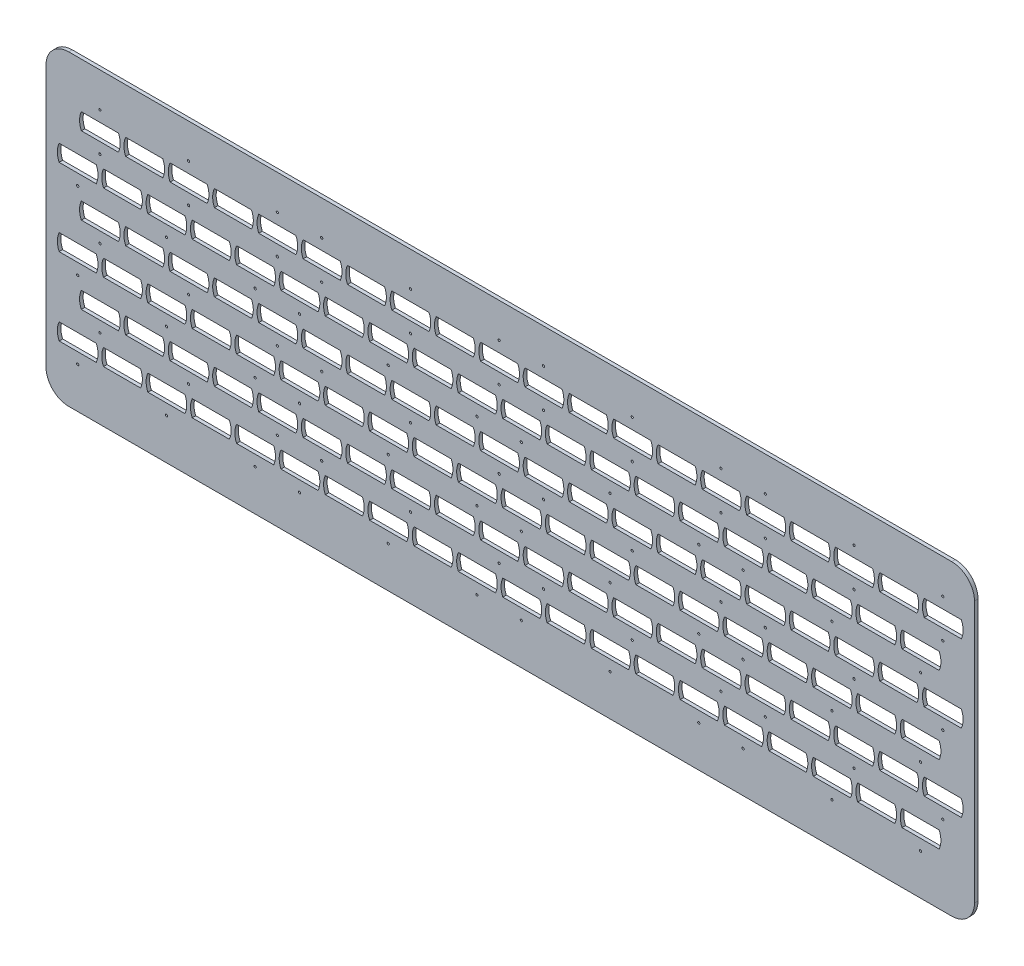
SolidWorks part; units mm, degrees
material "Custom Plastic"
ref_plane "X-Y Datum" through (0, 0, 0) normal (0, 0, 1) x (1, 0, 0)
ref_plane "X-Z Datum" through (0, 0, 0) normal (0, 1, 0) x (1, 0, 0)
ref_plane "Y-Z Datum" through (0, 0, 0) normal (1, 0, 0) x (0, 0, -1)
sketch "Sketch1" plane through (0, 0, 0) normal (0, 0, 1) x (1, 0, 0)
  line L0 (0, 0) -> (0, 17.78) construction
  line L1 (0, 0) -> (414.644, 0)
  line L2 (0, 0) -> (0, 137.1309)
  line L3 (0, 137.1309) -> (414.644, 137.1309)
  line L4 (414.644, 0) -> (414.644, 137.1309)
  line L5 (400.489, 122.1757) -> (400.489, 137.1309) construction
  line L6 (409.564, 113.1007) -> (414.644, 113.1007) construction
  line L7 (14.155, 17.78) -> (14.155, 0) construction
  line L8 (5.08, 26.855) -> (0, 26.855) construction
  circle A0 centre (14.155, 26.855) radius 9.075
  circle A1 centre (33.967, 26.855) radius 9.075
  circle A2 centre (53.779, 26.855) radius 9.075
  circle A3 centre (73.591, 26.855) radius 9.075
  circle A4 centre (93.403, 26.855) radius 9.075
  circle A5 centre (113.215, 26.855) radius 9.075
  circle A6 centre (133.027, 26.855) radius 9.075
  circle A7 centre (152.839, 26.855) radius 9.075
  circle A8 centre (172.651, 26.855) radius 9.075
  circle A9 centre (192.463, 26.855) radius 9.075
  circle A10 centre (212.275, 26.855) radius 9.075
  circle A11 centre (232.087, 26.855) radius 9.075
  circle A12 centre (251.899, 26.855) radius 9.075
  circle A13 centre (271.711, 26.855) radius 9.075
  circle A14 centre (291.523, 26.855) radius 9.075
  circle A15 centre (311.335, 26.855) radius 9.075
  circle A16 centre (331.147, 26.855) radius 9.075
  circle A17 centre (350.959, 26.855) radius 9.075
  circle A18 centre (370.771, 26.855) radius 9.075
  circle A19 centre (390.583, 26.855) radius 9.075
  circle A20 centre (43.873, 44.0127) radius 9.075
  circle A21 centre (63.685, 44.0127) radius 9.075
  circle A22 centre (83.497, 44.0127) radius 9.075
  circle A23 centre (103.309, 44.0127) radius 9.075
  circle A24 centre (123.121, 44.0127) radius 9.075
  circle A25 centre (142.933, 44.0127) radius 9.075
  circle A26 centre (162.745, 44.0127) radius 9.075
  circle A27 centre (182.557, 44.0127) radius 9.075
  circle A28 centre (202.369, 44.0127) radius 9.075
  circle A29 centre (222.181, 44.0127) radius 9.075
  circle A30 centre (241.993, 44.0127) radius 9.075
  circle A31 centre (261.805, 44.0127) radius 9.075
  circle A32 centre (281.617, 44.0127) radius 9.075
  circle A33 centre (301.429, 44.0127) radius 9.075
  circle A34 centre (321.241, 44.0127) radius 9.075
  circle A35 centre (341.053, 44.0127) radius 9.075
  circle A36 centre (360.865, 44.0127) radius 9.075
  circle A37 centre (380.677, 44.0127) radius 9.075
  circle A38 centre (400.489, 44.0127) radius 9.075
  circle A39 centre (24.061, 44.0127) radius 9.075
  circle A40 centre (14.155, 61.399) radius 9.075
  circle A41 centre (33.967, 61.399) radius 9.075
  circle A42 centre (53.779, 61.399) radius 9.075
  circle A43 centre (73.591, 61.399) radius 9.075
  circle A44 centre (93.403, 61.399) radius 9.075
  circle A45 centre (113.215, 61.399) radius 9.075
  circle A46 centre (133.027, 61.399) radius 9.075
  circle A47 centre (152.839, 61.399) radius 9.075
  circle A48 centre (172.651, 61.399) radius 9.075
  circle A49 centre (192.463, 61.399) radius 9.075
  circle A50 centre (212.275, 61.399) radius 9.075
  circle A51 centre (232.087, 61.399) radius 9.075
  circle A52 centre (251.899, 61.399) radius 9.075
  circle A53 centre (271.711, 61.399) radius 9.075
  circle A54 centre (291.523, 61.399) radius 9.075
  circle A55 centre (311.335, 61.399) radius 9.075
  circle A56 centre (331.147, 61.399) radius 9.075
  circle A57 centre (350.959, 61.399) radius 9.075
  circle A58 centre (370.771, 61.399) radius 9.075
  circle A59 centre (390.583, 61.399) radius 9.075
  circle A60 centre (43.873, 78.5567) radius 9.075
  circle A61 centre (63.685, 78.5567) radius 9.075
  circle A62 centre (83.497, 78.5567) radius 9.075
  circle A63 centre (103.309, 78.5567) radius 9.075
  circle A64 centre (123.121, 78.5567) radius 9.075
  circle A65 centre (142.933, 78.5567) radius 9.075
  circle A66 centre (162.745, 78.5567) radius 9.075
  circle A67 centre (182.557, 78.5567) radius 9.075
  circle A68 centre (202.369, 78.5567) radius 9.075
  circle A69 centre (222.181, 78.5567) radius 9.075
  circle A70 centre (241.993, 78.5567) radius 9.075
  circle A71 centre (261.805, 78.5567) radius 9.075
  circle A72 centre (281.617, 78.5567) radius 9.075
  circle A73 centre (301.429, 78.5567) radius 9.075
  circle A74 centre (321.241, 78.5567) radius 9.075
  circle A75 centre (341.053, 78.5567) radius 9.075
  circle A76 centre (360.865, 78.5567) radius 9.075
  circle A77 centre (380.677, 78.5567) radius 9.075
  circle A78 centre (400.489, 78.5567) radius 9.075
  circle A79 centre (24.061, 78.5567) radius 9.075
  circle A80 centre (14.155, 95.943) radius 9.075
  circle A81 centre (33.967, 95.943) radius 9.075
  circle A82 centre (53.779, 95.943) radius 9.075
  circle A83 centre (73.591, 95.943) radius 9.075
  circle A84 centre (93.403, 95.943) radius 9.075
  circle A85 centre (113.215, 95.943) radius 9.075
  circle A86 centre (133.027, 95.943) radius 9.075
  circle A87 centre (152.839, 95.943) radius 9.075
  circle A88 centre (172.651, 95.943) radius 9.075
  circle A89 centre (192.463, 95.943) radius 9.075
  circle A90 centre (212.275, 95.943) radius 9.075
  circle A91 centre (232.087, 95.943) radius 9.075
  circle A92 centre (251.899, 95.943) radius 9.075
  circle A93 centre (271.711, 95.943) radius 9.075
  circle A94 centre (291.523, 95.943) radius 9.075
  circle A95 centre (311.335, 95.943) radius 9.075
  circle A96 centre (331.147, 95.943) radius 9.075
  circle A97 centre (350.959, 95.943) radius 9.075
  circle A98 centre (370.771, 95.943) radius 9.075
  circle A99 centre (390.583, 95.943) radius 9.075
  circle A100 centre (43.873, 113.1007) radius 9.075
  circle A101 centre (63.685, 113.1007) radius 9.075
  circle A102 centre (83.497, 113.1007) radius 9.075
  circle A103 centre (103.309, 113.1007) radius 9.075
  circle A104 centre (123.121, 113.1007) radius 9.075
  circle A105 centre (142.933, 113.1007) radius 9.075
  circle A106 centre (162.745, 113.1007) radius 9.075
  circle A107 centre (182.557, 113.1007) radius 9.075
  circle A108 centre (202.369, 113.1007) radius 9.075
  circle A109 centre (222.181, 113.1007) radius 9.075
  circle A110 centre (241.993, 113.1007) radius 9.075
  circle A111 centre (261.805, 113.1007) radius 9.075
  circle A112 centre (281.617, 113.1007) radius 9.075
  circle A113 centre (301.429, 113.1007) radius 9.075
  circle A114 centre (321.241, 113.1007) radius 9.075
  circle A115 centre (341.053, 113.1007) radius 9.075
  circle A116 centre (360.865, 113.1007) radius 9.075
  circle A117 centre (380.677, 113.1007) radius 9.075
  circle A118 centre (400.489, 113.1007) radius 9.075
  circle A119 centre (24.061, 113.1007) radius 9.075
  dimension "D1" = 20
  dimension "D2" = 2
  dimension "D3" = 3
extrude "Plate thickness" add sketch "Sketch1" along normal blind 1.5748
sketch "Sketch2" plane through (0, 0, 1.5748) normal (0, 0, 1) x (1, 0, 0)
  line L0 (14.155, 23.155) -> (5.08, 23.155) construction
  line L5 (14.986, 40.3127) -> (14.986, 74.8567) construction
  line L14 (14.986, 40.3127) -> (114.046, 40.3127) construction
  line L15 (24.061, 23.155) -> (24.061, 40.3127) construction
  line L16 (5.08, 23.155) -> (409.564, 23.155)
  line L17 (5.08, 23.155) -> (5.08, 13.3973)
  line L18 (5.08, 13.3973) -> (409.564, 13.3973)
  line L19 (409.564, 23.155) -> (409.564, 13.3973)
  line L21 (5.08, 40.3127) -> (409.564, 40.3127)
  line L22 (5.08, 40.3127) -> (5.08, 30.555)
  line L23 (5.08, 30.555) -> (409.564, 30.555)
  line L24 (409.564, 40.3127) -> (409.564, 30.555)
  line L25 (5.08, 57.699) -> (409.564, 57.699)
  line L26 (5.08, 57.699) -> (5.08, 47.7127)
  line L27 (5.08, 47.7127) -> (409.564, 47.7127)
  line L28 (409.564, 57.699) -> (409.564, 47.7127)
  line L29 (5.08, 74.8567) -> (409.564, 74.8567)
  line L30 (5.08, 74.8567) -> (5.08, 65.099)
  line L31 (5.08, 65.099) -> (409.564, 65.099)
  line L32 (409.564, 74.8567) -> (409.564, 65.099)
  line L33 (5.08, 92.243) -> (409.564, 92.243)
  line L34 (5.08, 92.243) -> (5.08, 82.2567)
  line L35 (5.08, 82.2567) -> (409.564, 82.2567)
  line L36 (409.564, 92.243) -> (409.564, 82.2567)
  line L37 (5.08, 109.4007) -> (409.564, 109.4007)
  line L38 (5.08, 109.4007) -> (5.08, 99.643)
  line L39 (5.08, 99.643) -> (409.564, 99.643)
  line L40 (409.564, 109.4007) -> (409.564, 99.643)
  line L41 (5.08, 116.8007) -> (409.564, 116.8007)
  line L42 (5.08, 116.8007) -> (5.08, 126.5584)
  line L43 (5.08, 126.5584) -> (409.564, 126.5584)
  line L44 (409.564, 116.8007) -> (409.564, 126.5584)
  circle A0 centre (14.155, 26.855) radius 3.7 construction
  circle A1 centre (24.061, 44.0127) radius 3.7 construction
  circle A2 centre (24.061, 78.5567) radius 3.7 construction
  circle A3 centre (123.121, 44.0127) radius 3.7 construction
  circle A4 centre (14.155, 61.399) radius 3.7 construction
  circle A5 centre (14.155, 95.943) radius 3.7 construction
  circle A6 centre (24.061, 113.1007) radius 3.7 construction
extrude "Busbar Width" add sketch "Sketch2" against normal through all
sketch "Sketch3" plane through (0, 0, 1.5748) normal (0, 0, 1) x (1, 0, 0)
  line L0 (104.9285, 30.555) -> (121.5015, 30.555) construction
  line L1 (5.8685, 23.155) -> (101.6895, 23.155) construction
  line L2 (5.8685, 23.155) -> (5.8685, 13.3973) construction
  line L3 (5.8685, 13.3973) -> (101.6895, 13.3973) construction
  line L4 (101.6895, 23.155) -> (101.6895, 13.3973) construction
  line L5 (15.7745, 40.3127) -> (112.384, 40.3127) construction
  line L6 (15.7745, 40.3127) -> (15.7745, 30.555) construction
  line L7 (15.7745, 30.555) -> (112.384, 30.555) construction
  line L8 (112.384, 40.3127) -> (112.384, 30.555) construction
  line L9 (24.061, 47.7127) -> (24.061, 35.4338) construction
  line L10 (15.7745, 47.7127) -> (32.3475, 47.7127) construction
  line L11 (63.685, 47.7127) -> (63.685, 35.4338) construction
  line L12 (55.3985, 47.7127) -> (71.9715, 47.7127) construction
  line L13 (103.309, 47.7127) -> (103.309, 35.4338) construction
  line L14 (95.0225, 47.7127) -> (111.5955, 47.7127) construction
  line L15 (14.155, 30.555) -> (14.155, 15.8064) construction
  line L16 (5.8685, 30.555) -> (22.4415, 30.555) construction
  line L17 (5.8685, 18.2762) -> (14.155, 18.2762) construction
  line L18 (53.779, 23.155) -> (53.779, 18.2762) construction
  line L19 (93.403, 26.855) -> (93.403, 18.2762) construction
  line L20 (14.155, 18.2762) -> (113.215, 18.2762) construction
  line L21 (5.8685, 57.699) -> (5.8685, 47.7127) construction
  line L22 (15.7745, 47.7127) -> (5.8685, 47.7127) construction
  line L23 (15.7745, 74.8567) -> (15.7745, 65.099) construction
  line L24 (5.8685, 65.099) -> (22.4415, 65.099) construction
  line L25 (15.7745, 82.2567) -> (15.7745, 92.243) construction
  line L26 (22.4415, 92.243) -> (5.8685, 92.243) construction
  line L27 (15.7745, 109.4007) -> (15.7745, 99.643) construction
  line L28 (5.8685, 99.643) -> (22.4415, 99.643) construction
  line L29 (15.7745, 116.8007) -> (15.7745, 126.5584) construction
  line L30 (14.986, 35.4338) -> (24.061, 35.4338) construction
  line L31 (14.986, 40.3127) -> (112.384, 40.3127) construction
  line L32 (14.986, 40.3127) -> (14.986, 30.555) construction
  line L33 (14.986, 30.555) -> (112.384, 30.555) construction
  line L34 (112.384, 40.3127) -> (112.384, 30.555) construction
  circle A0 centre (14.155, 18.2762) radius 0.5
  circle A1 centre (53.779, 18.2762) radius 0.5
  circle A2 centre (93.403, 18.2762) radius 0.5
  circle A3 centre (24.061, 35.4338) radius 0.5
  circle A4 centre (63.685, 35.4338) radius 0.5
  circle A5 centre (103.309, 35.4338) radius 0.5
  circle A6 centre (113.215, 18.2762) radius 0.5
  circle A7 centre (152.839, 18.2762) radius 0.5
  circle A8 centre (192.463, 18.2762) radius 0.5
  circle A9 centre (202.369, 35.4338) radius 0.5
  circle A10 centre (162.745, 35.4338) radius 0.5
  circle A11 centre (123.121, 35.4338) radius 0.5
  circle A12 centre (212.275, 18.2762) radius 0.5
  circle A13 centre (251.899, 18.2762) radius 0.5
  circle A14 centre (291.523, 18.2762) radius 0.5
  circle A15 centre (301.429, 35.4338) radius 0.5
  circle A16 centre (261.805, 35.4338) radius 0.5
  circle A17 centre (222.181, 35.4338) radius 0.5
  circle A18 centre (311.335, 18.2762) radius 0.5
  circle A19 centre (350.959, 18.2762) radius 0.5
  circle A20 centre (390.583, 18.2762) radius 0.5
  circle A21 centre (400.489, 35.4338) radius 0.5
  circle A22 centre (360.865, 35.4338) radius 0.5
  circle A23 centre (321.241, 35.4338) radius 0.5
  circle A24 centre (14.155, 52.7058) radius 0.5
  circle A25 centre (53.779, 52.7058) radius 0.5
  circle A26 centre (93.403, 52.7058) radius 0.5
  circle A27 centre (24.061, 69.9778) radius 0.5
  circle A28 centre (63.685, 69.9778) radius 0.5
  circle A29 centre (103.309, 69.9778) radius 0.5
  circle A30 centre (14.155, 87.2498) radius 0.5
  circle A31 centre (53.779, 87.2498) radius 0.5
  circle A32 centre (93.403, 87.2498) radius 0.5
  circle A33 centre (24.061, 104.5218) radius 0.5
  circle A34 centre (63.685, 104.5218) radius 0.5
  circle A35 centre (103.309, 104.5218) radius 0.5
  circle A36 centre (24.061, 121.6795) radius 0.5
  circle A38 centre (63.685, 121.6795) radius 0.5
  circle A39 centre (103.309, 121.6795) radius 0.5
  circle A40 centre (113.215, 52.7058) radius 0.5
  circle A41 centre (152.839, 52.7058) radius 0.5
  circle A42 centre (192.463, 52.7058) radius 0.5
  circle A43 centre (202.369, 69.9778) radius 0.5
  circle A44 centre (162.745, 69.9778) radius 0.5
  circle A45 centre (123.121, 69.9778) radius 0.5
  circle A46 centre (113.215, 87.2498) radius 0.5
  circle A47 centre (192.463, 87.2498) radius 0.5
  circle A48 centre (152.839, 87.2498) radius 0.5
  circle A49 centre (123.121, 104.5218) radius 0.5
  circle A50 centre (123.121, 121.6795) radius 0.5
  circle A51 centre (162.745, 121.6795) radius 0.5
  circle A52 centre (162.745, 104.5218) radius 0.5
  circle A53 centre (202.369, 104.5218) radius 0.5
  circle A54 centre (202.369, 121.6795) radius 0.5
  circle A55 centre (212.275, 52.7058) radius 0.5
  circle A56 centre (251.899, 52.7058) radius 0.5
  circle A57 centre (291.523, 52.7058) radius 0.5
  circle A58 centre (301.429, 69.9778) radius 0.5
  circle A59 centre (261.805, 69.9778) radius 0.5
  circle A60 centre (222.181, 69.9778) radius 0.5
  circle A61 centre (212.275, 87.2498) radius 0.5
  circle A62 centre (291.523, 87.2498) radius 0.5
  circle A63 centre (251.899, 87.2498) radius 0.5
  circle A64 centre (222.181, 104.5218) radius 0.5
  circle A65 centre (222.181, 121.6795) radius 0.5
  circle A66 centre (261.805, 121.6795) radius 0.5
  circle A67 centre (261.805, 104.5218) radius 0.5
  circle A68 centre (301.429, 104.5218) radius 0.5
  circle A69 centre (301.429, 121.6795) radius 0.5
  circle A70 centre (311.335, 52.7058) radius 0.5
  circle A71 centre (350.959, 52.7058) radius 0.5
  circle A72 centre (390.583, 52.7058) radius 0.5
  circle A73 centre (400.489, 69.9778) radius 0.5
  circle A74 centre (360.865, 69.9778) radius 0.5
  circle A75 centre (321.241, 69.9778) radius 0.5
  circle A76 centre (311.335, 87.2498) radius 0.5
  circle A77 centre (390.583, 87.2498) radius 0.5
  circle A78 centre (350.959, 87.2498) radius 0.5
  circle A79 centre (321.241, 104.5218) radius 0.5
  circle A80 centre (321.241, 121.6795) radius 0.5
  circle A81 centre (360.865, 121.6795) radius 0.5
  circle A82 centre (360.865, 104.5218) radius 0.5
  circle A83 centre (400.489, 104.5218) radius 0.5
  circle A84 centre (400.489, 121.6795) radius 0.5
  dimension "D1" = 4
extrude "Cut-Extrude1" cut sketch "Sketch3" against normal through all
fillet "Fillet1" radius 10.16 4 edges at (414.644, 0, 0.7874) (414.644, 137.1309, 0.7874) (0, 137.1309, 0.7874) (0, 0, 0.7874)
